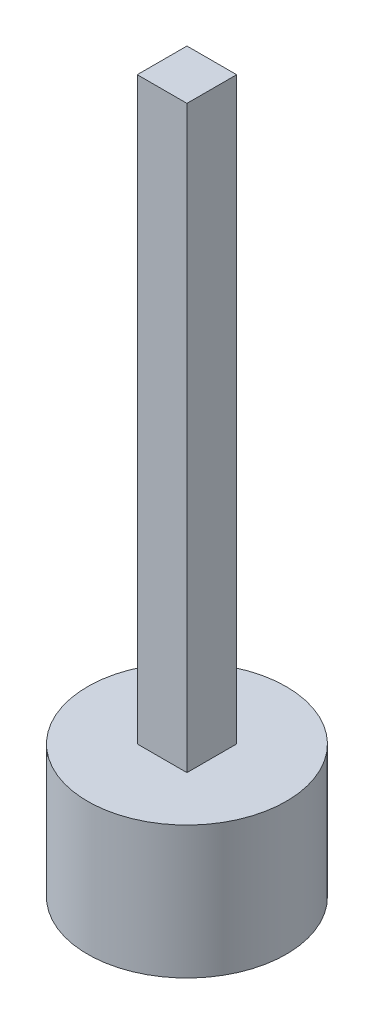
SolidWorks part; units mm, degrees
ref_plane "Front Plane" through (0, 0, 0) normal (0, 0, 1) x (1, 0, 0)
ref_plane "Top Plane" through (0, 0, 0) normal (0, 1, 0) x (1, 0, 0)
ref_plane "Right Plane" through (0, 0, 0) normal (1, 0, 0) x (0, 0, -1)
sketch "Sketch1" plane through (0, 0, 0) normal (0, 1, 0) x (1, 0, 0)
  line L1 (15, 0) -> (-15, 0)
  line L2 (15, 0) -> (15, 30)
  line L3 (15, 30) -> (-15, 30)
  line L4 (-15, 0) -> (-15, 30)
  dimension "D1" = 30
extrude "Boss-Extrude1" add sketch "Sketch1" against normal blind 350
sketch "Sketch2" plane through (0, -350, 0) normal (0, -1, 0) x (1, 0, 0)
  line L0 (0, 0) -> (0, -30)
  line L1 (-15, 0) -> (15, 0) construction
  line L2 (15, -30) -> (-15, -30) construction
  line L3 (-15, -15) -> (15, -15)
  line L4 (-15, -30) -> (-15, 0) construction
  line L5 (15, 0) -> (15, -30) construction
  circle A0 centre (0, -15) radius 60
  dimension "D1" = 120
extrude "Boss-Extrude2" add sketch "Sketch2" along normal blind 80 contours A0
sketch "Sketch3" plane through (0, -430, 0) normal (0, -1, 0) x (1, 0, 0)
  circle A0 centre (0, -15) radius 60 construction
  point P0 (0, -15)
